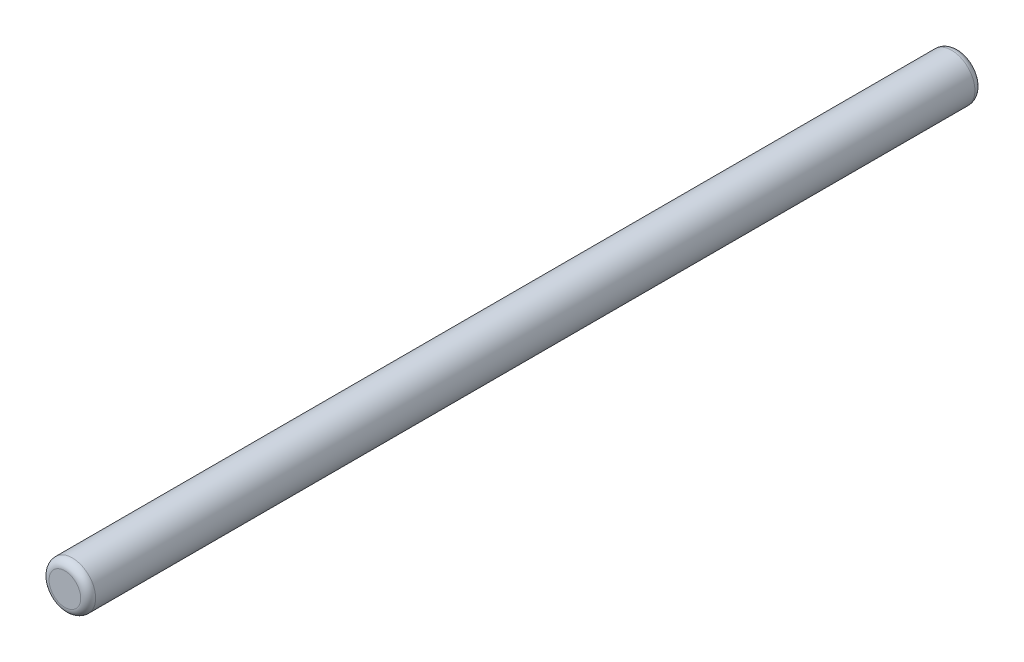
SolidWorks part; units mm, degrees
material "Alloy Steel"
ref_plane "Front Plane" through (0, 0, 0) normal (0, 0, 1) x (1, 0, 0)
ref_plane "Top Plane" through (0, 0, 0) normal (0, 1, 0) x (1, 0, 0)
ref_plane "Right Plane" through (0, 0, 0) normal (1, 0, 0) x (0, 0, -1)
sketch "Sketch1" plane through (0, 0, 0) normal (0, 0, 1) x (1, 0, 0)
  circle A0 centre (0, 0) radius 2.5
  dimension "D1" = 5
extrude "Boss-Extrude1" add sketch "Sketch1" along normal blind 96
fillet "Fillet1" radius 0.8 1 edges at (2.5, 0, 96)
fillet "Fillet2" radius 0.8 1 edges at (2.5, 0, 0)
